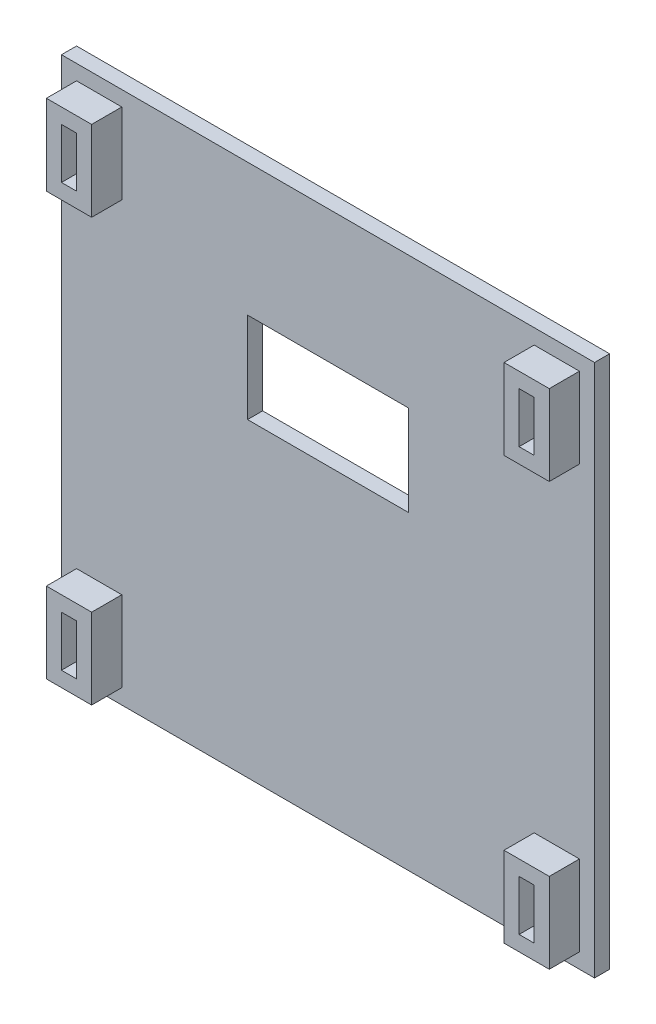
SolidWorks part; units mm, degrees
ref_plane "Front Plane" through (0, 0, 0) normal (0, 0, 1) x (1, 0, 0)
ref_plane "Top Plane" through (0, 0, 0) normal (0, 1, 0) x (1, 0, 0)
ref_plane "Right Plane" through (0, 0, 0) normal (1, 0, 0) x (0, 0, -1)
ref_plane "Plane1" through (0, 0, 1.5) normal (0, 0, 1) x (1, 0, 0)
sketch "Sketch1" plane through (0, 0, 1.5) normal (0, 0, 1) x (1, 0, 0)
  line L0 (53, 0) -> (53, 53)
  line L1 (53, 53) -> (0, 53)
  line L2 (0, 53) -> (0, 0)
  line L3 (0, 0) -> (53, 0)
extrude "Boss-Extrude1" add sketch "Sketch1" against normal blind 1.5
sketch "Sketch2" plane through (0, 0, 0) normal (0, 0, -1) x (-1, 0, 0)
  line L0 (-18.5, 39.8333) -> (-34.5, 39.8333)
  line L1 (-34.5, 39.8333) -> (-34.5, 30.8333)
  line L2 (-34.5, 30.8333) -> (-18.5, 30.8333)
  line L3 (-18.5, 30.8333) -> (-18.5, 39.8333)
extrude "Cut-Extrude1" cut sketch "Sketch2" against normal through all
ref_plane "Plane2" through (26.5, 0, 0) normal (-1, 0, 0) x (0, 0, 1)
ref_plane "Plane3" through (0, 26.5, 0) normal (0, 1, 0) x (1, 0, 0)
sketch "Sketch3" plane through (0, 0, 1.5) normal (0, 0, 1) x (1, 0, 0)
  line L0 (6, 43.5) -> (1.5, 43.5)
  line L1 (1.5, 43.5) -> (1.5, 51.5)
  line L2 (1.5, 51.5) -> (6, 51.5)
  line L3 (6, 51.5) -> (6, 43.5)
  line L4 (1.5, 51.5) -> (1.5, 1.5) construction
  line L5 (51.5, 51.5) -> (1.5, 51.5) construction
  line L6 (1.5, 51.5) -> (1.5, 1.5) construction
  line L7 (51.5, 51.5) -> (1.5, 51.5) construction
  dimension "D1" = 4.5
  dimension "D2" = 8
extrude "Boss-Extrude2" add sketch "Sketch3" along normal blind 3
sketch "Sketch4" plane through (0, 0, 4.5) normal (0, 0, 1) x (1, 0, 0)
  line L0 (4.5, 50) -> (3, 50)
  line L1 (3, 50) -> (3, 45)
  line L2 (3, 45) -> (4.5, 45)
  line L3 (4.5, 45) -> (4.5, 50)
  line L4 (3.75, 50) -> (3.75, 51.5) construction
  line L5 (3, 47.5) -> (1.5, 47.5) construction
  line L6 (4.5, 47.5) -> (6, 47.5) construction
  line L7 (3.75, 45) -> (3.75, 43.5) construction
  line L8 (6, 43.5) -> (6, 51.5)
  line L9 (6, 51.5) -> (1.5, 51.5)
  line L10 (1.5, 51.5) -> (1.5, 43.5)
  line L11 (1.5, 43.5) -> (6, 43.5)
  line L12 (6, 43.5) -> (6, 51.5) construction
  line L13 (6, 51.5) -> (1.5, 51.5) construction
  line L14 (1.5, 51.5) -> (1.5, 43.5) construction
  line L15 (1.5, 43.5) -> (6, 43.5) construction
  point P16 (4.5, 47.9836)
  point P17 (4.5, 47.5)
  point P18 (0, 0)
  point P19 (3, 47.5)
  point P20 (0, 0)
  point P21 (3.75, 45)
  dimension "D2" = 1.5
  dimension "D3" = 5
  dimension "D1" = 0
extrude "Cut-Extrude2" cut sketch "Sketch4" against normal blind 3
mirror "Mirror1" about plane through (26.5, 0, 0) normal (-1, 0, 0) of "Cut-Extrude2", "Boss-Extrude2"
mirror "Mirror2" about plane through (0, 26.5, 0) normal (0, 1, 0) of "Mirror1", "Cut-Extrude2", "Boss-Extrude2"
